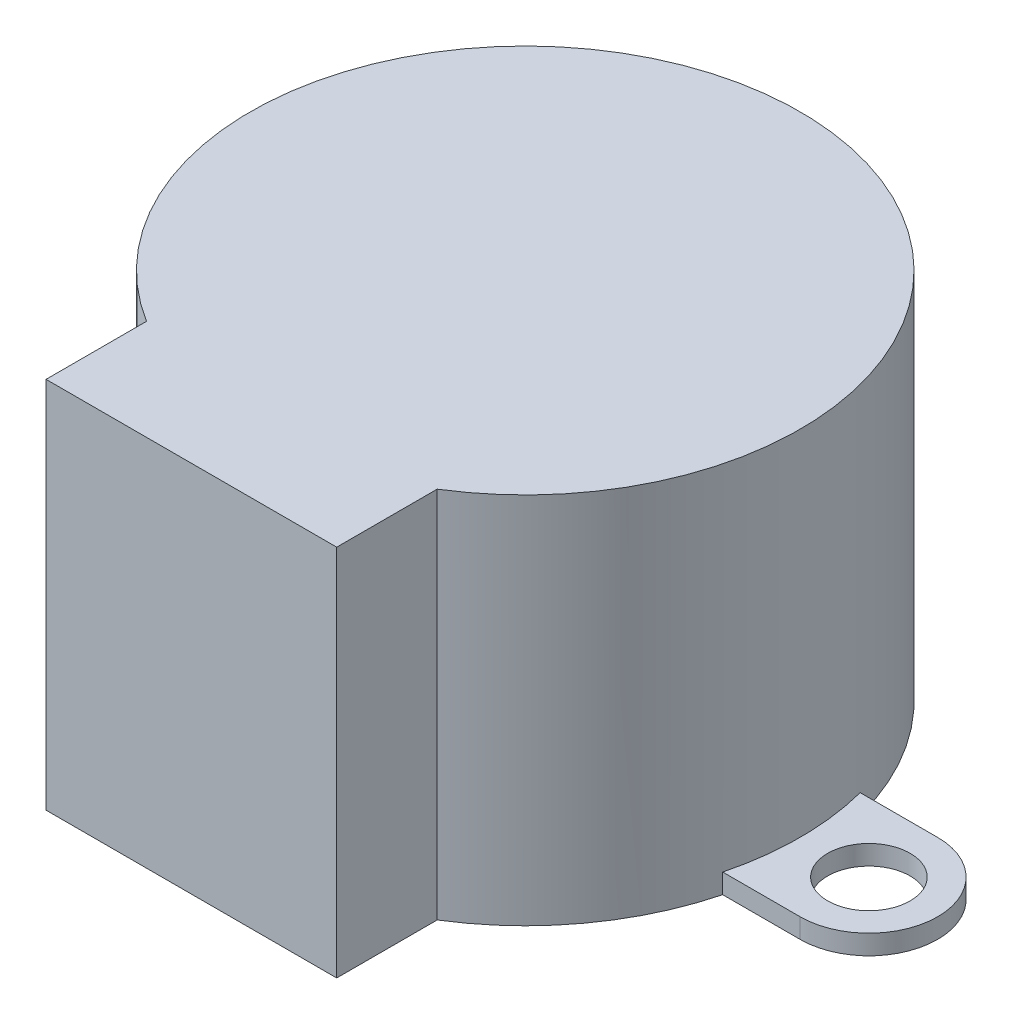
SolidWorks part; units mm, degrees
ref_plane "Front Plane" through (0, 0, 0) normal (0, 0, 1) x (1, 0, 0)
ref_plane "Top Plane" through (0, 0, 0) normal (0, 1, 0) x (1, 0, 0)
ref_plane "Right Plane" through (0, 0, 0) normal (1, 0, 0) x (0, 0, -1)
sketch "Sketch1" plane through (0, 0, 0) normal (0, 1, 0) x (1, 0, 0)
  line L0 (0, 0) -> (0, 24.95) construction
  line L1 (-7.4, -17) -> (-7.4, -11.8844)
  line L2 (-7.4, -17) -> (7.4, -17)
  line L4 (7.4, -17) -> (7.4, -11.8844)
  arc A0 (7.4, -11.8844) -> (-7.4, -11.8844) centre (0, 0) ccw
  point P4 (0, -8.5)
  dimension "D1" = 28
  dimension "D3" = 14.8
extrude "Boss-Extrude1" add sketch "Sketch1" along normal blind 19
sketch "Sketch2" plane through (0, 0, 0) normal (0, -1, 0) x (1, 0, 0)
  line L0 (0, -14) -> (0, 17) construction
  line L1 (-7.4, 17) -> (7.4, 17) construction
  line L2 (13.5554, -3.5) -> (13.5554, 3.5)
  line L3 (-17.5, -3.5) -> (-13.5554, -3.5)
  line L4 (17.5, 3.5) -> (13.5554, 3.5)
  line L5 (-17.5, 3.5) -> (-13.5554, 3.5)
  line L6 (-13.5554, -3.5) -> (-13.5554, 3.5)
  line L7 (17.5, -3.5) -> (13.5554, -3.5)
  circle A0 centre (-17.5, 0) radius 2.1
  arc A1 (-7.4, 11.8844) -> (7.4, 11.8844) centre (0, 0) ccw construction
  arc A2 (-17.5, 3.5) -> (-17.5, -3.5) centre (-17.5, 0) ccw
  arc A3 (17.5, 3.5) -> (17.5, -3.5) centre (17.5, 0) cw
  circle A4 centre (17.5, 0) radius 2.1
  dimension "D1" = 7
  dimension "D2" = 4.2
  dimension "D3" = 17.5
  dimension "D4" = 7
extrude "Boss-Extrude2" add sketch "Sketch2" against normal blind 1
sketch "Sketch3" plane through (0, 0, 0) normal (0, -1, 0) x (1, 0, 0)
  circle A0 centre (0, -8) radius 4.5
  dimension "D1" = 9
  dimension "D2" = 8
extrude "Boss-Extrude3" add sketch "Sketch3" along normal blind 1.5
sketch "Sketch4" plane through (0, -1.5, 0) normal (0, -1, 0) x (1, 0, 0)
  circle A0 centre (0, -8) radius 2.5
  dimension "D1" = 5
extrude "Boss-Extrude4" add sketch "Sketch4" along normal blind 2.5
sketch "Sketch5" plane through (0, -4, 0) normal (0, -1, 0) x (1, 0, 0)
  line L2 (-1.5, -10) -> (-1.5, -6)
  line L4 (1.5, -10) -> (1.5, -6)
  arc A0 (-1.5, -10) -> (1.5, -10) centre (0, -8) ccw
  arc A1 (1.5, -6) -> (-1.5, -6) centre (0, -8) ccw
  dimension "D2" = 5
  dimension "D1" = 3
extrude "Boss-Extrude5" add sketch "Sketch5" along normal blind 6
